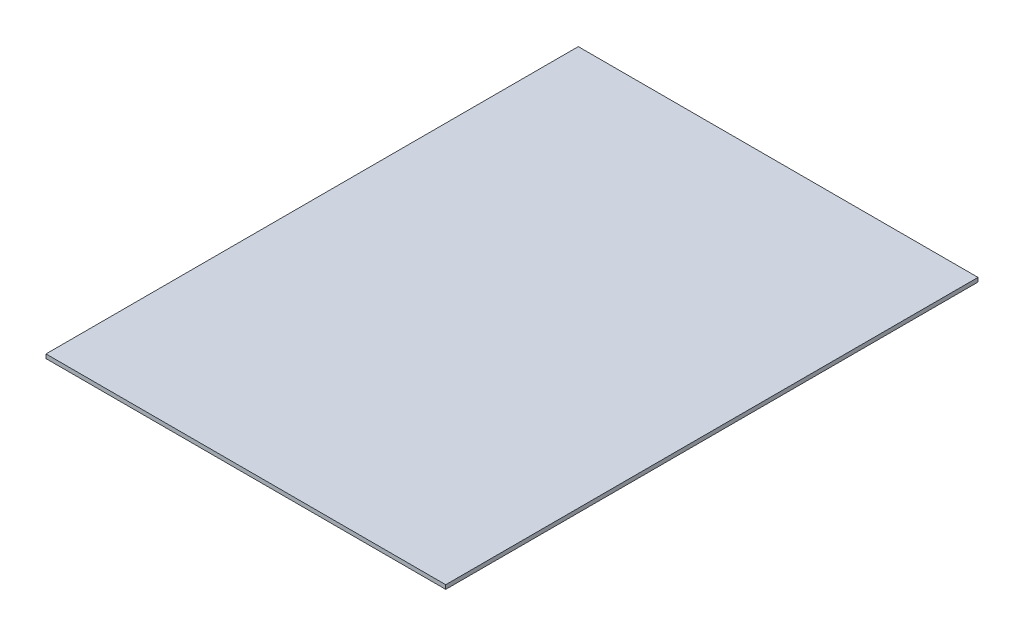
SolidWorks part; units mm, degrees
material "Pine"
ref_plane "Front Plane" through (0, 0, 0) normal (0, 0, 1) x (1, 0, 0)
ref_plane "Top Plane" through (0, 0, 0) normal (0, 1, 0) x (1, 0, 0)
ref_plane "Right Plane" through (0, 0, 0) normal (1, 0, 0) x (0, 0, -1)
sketch "Sketch1" plane through (0, 0, 0) normal (0, 1, 0) x (1, 0, 0)
  line L1 (0, 0) -> (622.3, 0)
  line L2 (0, 0) -> (0, 828.675)
  line L3 (0, 828.675) -> (622.3, 828.675)
  line L4 (622.3, 0) -> (622.3, 828.675)
  dimension "D1" = 622.3
  dimension "D2" = 828.675
extrude "Boss-Extrude1" add sketch "Sketch1" along normal blind 6.35
